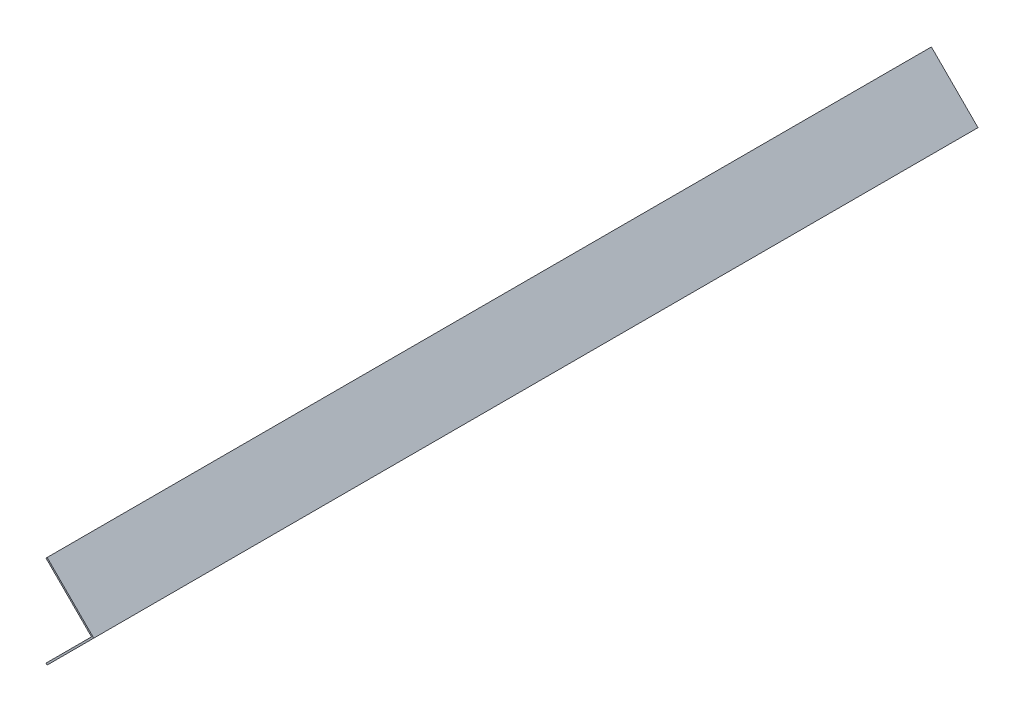
SolidWorks part; units mm, degrees
ref_plane "Front Plane" through (0, 0, 0) normal (0, 0, 1) x (1, 0, 0)
ref_plane "Top Plane" through (0, 0, 0) normal (0, 1, 0) x (1, 0, 0)
ref_plane "Right Plane" through (0, 0, 0) normal (1, 0, 0) x (0, 0, -1)
sketch "Sketch1" plane through (0, 0, 0) normal (0, 0, 1) x (1, 0, 0)
  line L0 (0, 0) -> (-28.2843, 28.2843)
  line L1 (0, 0) -> (-28.2843, -28.2843)
  line L2 (1.4142, 0) -> (-27.5772, 28.9914)
  line L3 (1.4142, 0) -> (-27.5772, -28.9914)
  line L4 (-27.5772, -28.9914) -> (-28.2843, -28.2843)
  line L5 (-28.2843, 28.2843) -> (-27.5772, 28.9914)
  dimension "D1" = 90
  dimension "D2" = 40
  dimension "D3" = 40
  dimension "D5" = 0
  dimension "D4" = 1
extrude "Boss-Extrude1" add sketch "Sketch1" along normal mid plane 550
